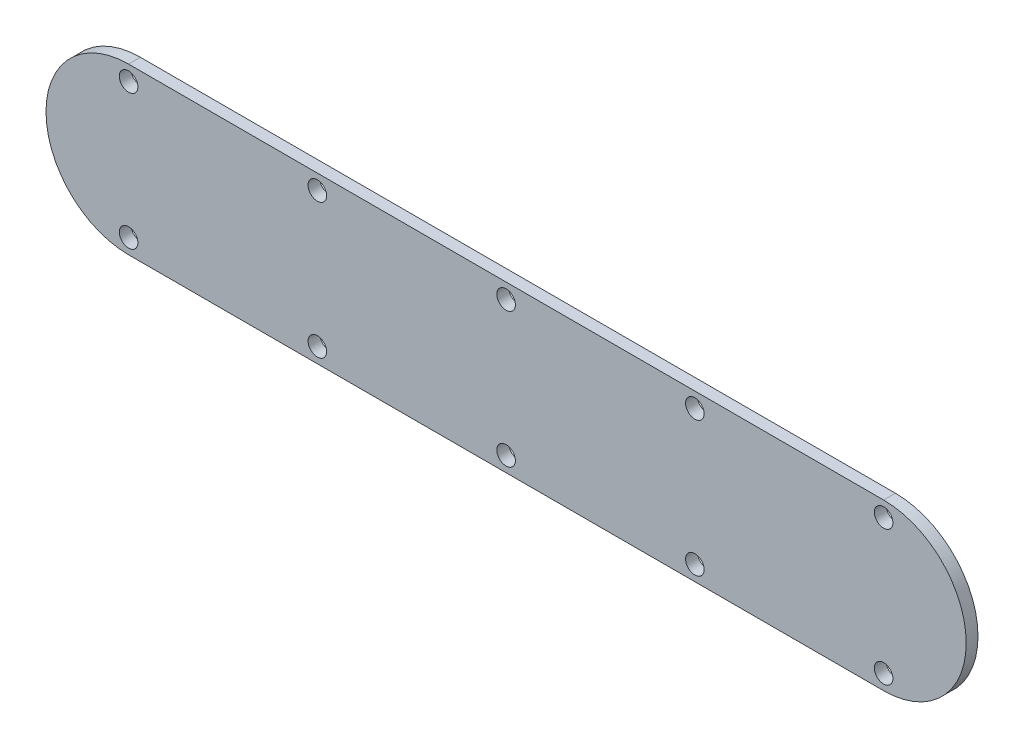
SolidWorks part; units mm, degrees
material "6061 Alloy"
ref_plane "Front" through (0, 0, 0) normal (0, 0, 1) x (1, 0, 0)
ref_plane "Top" through (0, 0, 0) normal (0, 1, 0) x (1, 0, 0)
ref_plane "Right" through (0, 0, 0) normal (1, 0, 0) x (0, 0, -1)
sketch "Sketch1" plane through (0, 0, 0) normal (0, 0, 1) x (1, 0, 0)
  line L1 (123.825, 22.225) -> (-123.825, 22.225)
  line L2 (123.825, 22.225) -> (123.825, -22.225)
  line L3 (123.825, -22.225) -> (-123.825, -22.225)
  line L4 (-123.825, 22.225) -> (-123.825, -22.225)
  line L5 (123.825, 22.225) -> (-123.825, -22.225) construction
  line L6 (123.825, -22.225) -> (-123.825, 22.225) construction
  point P0 (0, 0)
  dimension "D1" = 247.65
  dimension "D2" = 44.45
extrude "Boss-Extrude1" add sketch "Sketch1" along normal blind 3.175
sketch "Sketch2" plane through (0, 0, 3.175) normal (0, 0, 1) x (1, 0, 0)
  line L0 (101.6, 0) -> (-101.6, 0) construction
  line L1 (101.6, -14.351) -> (-101.6, -14.351)
  line L2 (101.6, 14.351) -> (-101.6, 14.351)
  line L3 (101.6, -22.225) -> (-101.6, -22.225)
  line L4 (101.6, 22.225) -> (-101.6, 22.225)
  arc A0 (101.6, -14.351) -> (101.6, 14.351) centre (101.6, 0) ccw
  arc A1 (-101.6, 14.351) -> (-101.6, -14.351) centre (-101.6, 0) ccw
  arc A2 (-101.6, 22.225) -> (-101.6, -22.225) centre (-101.6, 0) ccw
  arc A3 (101.6, -22.225) -> (101.6, 22.225) centre (101.6, 0) ccw
  point P2 (0, 0)
  line M9 (-123.825, 22.225) -> (-123.825, -22.225)
  line M10 (-123.825, -22.225) -> (123.825, -22.225)
  line M11 (123.825, -22.225) -> (123.825, 22.225)
  line M12 (123.825, 22.225) -> (-123.825, 22.225)
  dimension "D1" = 203.2
  dimension "D2" = 28.702
  dimension "D3" = 7.874
extrude "Cut-Extrude1" cut sketch "Sketch2" against normal through all contours A2 M12 M9 | A2 M9 M10 | A3 M10 M11 | A3 M11 M12
sketch "Sketch3" plane through (0, 0, 3.175) normal (0, 0, 1) x (1, 0, 0)
  line L2 (101.6, 18.161) -> (-101.6, 18.161)
  line L3 (101.6, 18.161) -> (-101.6, 18.161) construction
  line L4 (-101.6, 18.161) -> (0, 18.161) construction
  line L5 (-101.6, -18.161) -> (101.6, -18.161)
  line L6 (-101.6, -18.161) -> (101.6, -18.161) construction
  line L7 (0, 18.161) -> (101.6, 18.161) construction
  line L8 (-101.6, -18.161) -> (0, -18.161) construction
  line L9 (0, -18.161) -> (101.6, -18.161) construction
  point P0 (0, 18.161)
  point P1 (-101.6, 18.161)
  point P6 (0, -18.161)
  point P7 (101.6, 18.161)
  point P8 (101.6, -18.161)
  point P9 (-50.8, 18.161)
  point P10 (-101.6, -18.161)
  point P13 (50.8, 18.161)
  point P14 (-50.8, -18.161)
  point P15 (50.8, -18.161)
  dimension "D1" = 4.064
  dimension "D2" = 4.064
hole_wizard "#10 (0.1935) Diameter Hole1" positions "Sketch6" profile "Sketch7" hole size "#10" standard "ANSI Inch" end condition through all
sketch "Sketch6" plane through (0, 0, 3.175) normal (0, 0, 1) x (1, 0, 0)
  point P0 (-101.6, 18.161)
  point P3 (-50.8, 18.161)
  point P6 (0, 18.161)
  point P9 (50.8, 18.161)
  point P12 (101.6, 18.161)
  point P15 (101.6, -18.161)
  point P18 (50.8, -18.161)
  point P21 (0, -18.161)
  point P24 (-50.8, -18.161)
  point P27 (-101.6, -18.161)
sketch "Sketch7" plane through (-101.6, 18.161, 3.175) normal (1, 0, 0) x (0, -1, 0)
  line L0 (0, 0) -> (0, 3.175)
  line L1 (0, 3.175) -> (2.5, 3.175)
  line L2 (2.5, 3.175) -> (2.5, 0)
  line L5 (2.5, 0) -> (0, 0)
  line L11 (0, -6.35) -> (0, 107.95) construction
  dimension "Thru Hole Dia." = 5
  dimension "Thru Hole Depth" = 3.175
